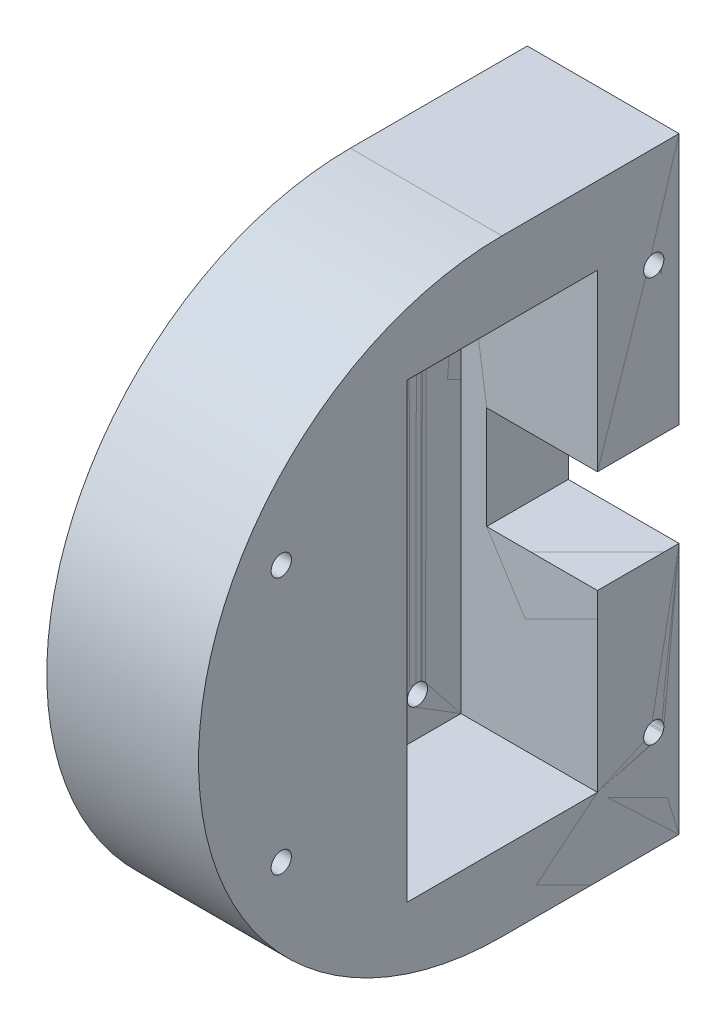
SolidWorks part; units mm, degrees
ref_plane "Plano frontal" through (0, 0, 0) normal (0, 0, 1) x (1, 0, 0)
ref_plane "Plano superior" through (0, 0, 0) normal (0, 1, 0) x (1, 0, 0)
ref_plane "Plano direito" through (0, 0, 0) normal (1, 0, 0) x (0, 0, -1)
sketch "Esboço34" plane through (0, 0, 5) normal (0, 0, 1) x (1, 0, 0)
  line L1 (55.1891, 10.4855) -> (70.1891, 10.4855)
  line L2 (55.1891, 10.4855) -> (55.1891, -49.5145)
  line L3 (55.1891, -49.5145) -> (70.1891, -49.5145)
  line L4 (70.1891, 10.4855) -> (70.1891, -49.5145)
extrude "Ressalto-extrusão9" add sketch "Esboço34" along normal blind 12.5 and the other way blind 5 separate body
sketch "Esboço35" plane through (70.1891, 0, 0) normal (1, 0, 0) x (0, 0, -1)
  line L4 (0, 10.4855) -> (-17.5, 10.4855)
  line L5 (-17.5, 10.4855) -> (-17.5, -49.5145)
  line L6 (-17.5, -49.5145) -> (0, -49.5145)
  line L7 (0, -49.5145) -> (0, 10.4855)
  line L8 (0, 10.4855) -> (-17.5, 10.4855)
  line L10 (-17.5, -49.5145) -> (0, -49.5145)
  line L11 (0, -49.5145) -> (0, 10.4855)
  arc A0 (-17.5, -49.5145) -> (-17.5, 10.4855) centre (-17.5, -19.5145) cw
  dimension "D1" = 0
extrude "Ressalto-extrusão10" add sketch "Esboço35" against normal blind 15 separate body
sketch "Esboço36" plane through (70.1891, 0, 0) normal (1, 0, 0) x (0, 0, -1)
  line L0 (-17.5, -49.5145) -> (0, -49.5145) construction
  line L1 (0, -49.5145) -> (0, 10.4855) construction
  circle A0 centre (-2.5, -39.5145) radius 1
  circle A2 centre (-2.5, 0.4855) radius 1
  dimension "D1" = 10
  dimension "D2" = 2.5
  dimension "D5" = 2.5
  dimension "D6" = 50
extrude "Corte-extrusão18" cut sketch "Esboço36" against normal blind 20
sketch "Esboço39" plane through (70.1891, 0, 0) normal (1, 0, 0) x (0, 0, -1)
  line L1 (-26.9163, -41.876) -> (-8.0663, -41.876)
  line L2 (-26.9163, -41.876) -> (-26.9163, 2.829)
  line L3 (-26.9163, 2.829) -> (-8.0663, 2.829)
  line L4 (-8.0663, -41.876) -> (-8.0663, 2.829)
extrude "Corte-extrusão20" cut sketch "Esboço39" against normal blind 13.49
sketch "Esboço41" plane through (56.6991, 0, 0) normal (1, 0, 0) x (0, 0, -1)
  line L0 (-8.0663, 2.829) -> (-26.9163, 2.829) construction
  line L1 (-26.9163, 2.829) -> (-26.9163, -41.876) construction
  circle A0 centre (-20.3753, -0.981) radius 1.6255
  circle A1 centre (-12.3753, -0.981) radius 1
  dimension "D1" = 3.81
  dimension "D2" = 6.541
  dimension "D3" = 8
sketch "Esboço42" plane through (56.6991, 0, 0) normal (1, 0, 0) x (0, 0, -1)
  line L0 (-26.9163, 2.829) -> (-26.9163, -41.876) construction
  line L1 (-26.9163, -41.876) -> (-8.0663, -41.876) construction
  circle A0 centre (-20.3753, -38.066) radius 1.6255
  circle A1 centre (-12.3753, -38.066) radius 1
  dimension "D1" = 6.541
  dimension "D3" = 8
  dimension "D2" = 3.81
sketch "Esboço43" plane through (0, 0, 8.0663) normal (0, 0, 1) x (1, 0, 0)
  line L1 (59.2391, -24.5945) -> (70.1891, -24.5945)
  line L2 (59.2391, -24.5945) -> (59.2391, -14.4345)
  line L3 (59.2391, -14.4345) -> (70.1891, -14.4345)
  line L4 (70.1891, -24.5945) -> (70.1891, -14.4345)
  line L6 (56.6991, -41.876) -> (56.6991, 2.829) construction
  line L7 (55.1891, -49.5145) -> (70.1891, -49.5145) construction
  line L8 (70.1891, 10.4855) -> (55.1891, 10.4855) construction
  line L9 (70.1891, -41.876) -> (70.1891, 2.829) construction
  point P8 (64.7141, -14.4345)
  dimension "D1" = 2.54
  dimension "D2" = 24.92
  dimension "D3" = 24.92
extrude "Corte-extrusão23" cut sketch "Esboço43" against normal blind 10
sketch "Esboço62" plane through (70.1891, 0, 0) normal (1, 0, 0) x (0, 0, -1)
  circle A2 centre (-39.32, -32.23) radius 1
  circle A4 centre (-39.32, -6.7995) radius 1
  dimension "D2" = 8.13
extrude "Corte-extrusão33" cut sketch "Esboço41" along normal blind 20 and the other way blind 10
extrude "Corte-extrusão34" cut sketch "Esboço42" against normal blind 20
extrude "Corte-extrusão35" cut sketch "Esboço62" against normal blind 20
